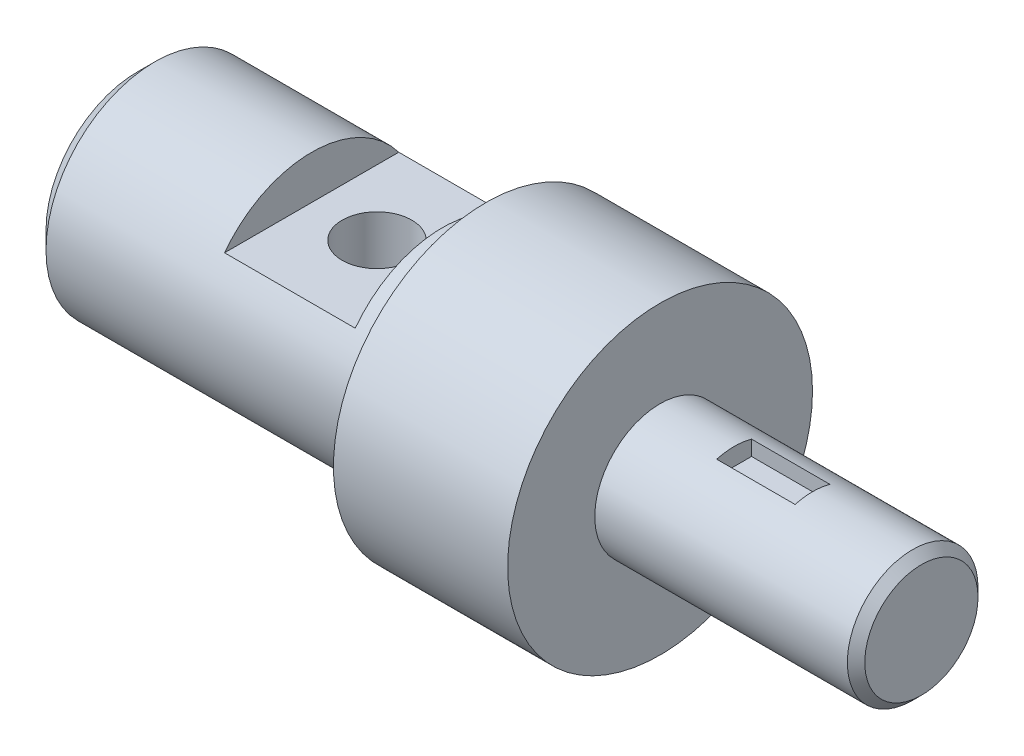
SolidWorks part; units mm, degrees
ref_plane "Спереди" through (0, 0, 0) normal (0, 0, 1) x (1, 0, 0)
ref_plane "Сверху" through (0, 0, 0) normal (0, 1, 0) x (1, 0, 0)
ref_plane "Справа" through (0, 0, 0) normal (1, 0, 0) x (0, 0, -1)
sketch "Эскиз1" plane through (0, 0, 0) normal (0, 0, 1) x (1, 0, 0)
  line L1 (0, 0) -> (0, 25)
  line L2 (0, 25) -> (80, 25)
  line L3 (80, 25) -> (80, 35)
  line L4 (80, 35) -> (120, 35)
  line L5 (120, 35) -> (120, 15)
  line L6 (120, 15) -> (180, 15)
  line L7 (180, 15) -> (180, 0)
  line L8 (0, 0) -> (180, 0)
  line L9 (0, 0) -> (-45.0163, 0) construction
  dimension "D1" = 70
  dimension "D2" = 50
  dimension "D3" = 30
  dimension "D4" = 180
  dimension "D5" = 80
  dimension "D6" = 60
revolve "Повернуть1" add sketch "Эскиз1" angle 360 about L9
sketch "Эскиз10" plane through (0, 0, 0) normal (0, 0, 1) x (1, 0, 0)
  line L0 (80, 25) -> (0, 25) construction
  line L1 (40, 25) -> (70, 25)
  line L2 (40, 25) -> (40, 15)
  line L3 (40, 15) -> (70, 15)
  line L4 (70, 25) -> (70, 15)
  line L5 (0, 25) -> (0, -25) construction
  line L6 (0, -25) -> (80, -25) construction
  dimension "D1" = 40
  dimension "D2" = 30
  dimension "D3" = 40
extrude "Вырез-Вытянуть7" cut sketch "Эскиз10" against normal through all both and the other way through all
ref_plane "Плоскость4" through (0, 35, 0) normal (0, 1, 0) x (1, 0, 0)
sketch "Эскиз14" plane through (0, 15, 0) normal (0, 1, 0) x (1, 0, 0)
  line L0 (40, 0) -> (70, 0) construction
  line L1 (40, -20) -> (40, 20) construction
  line L2 (70, 20) -> (70, -20) construction
  circle A0 centre (55, 0) radius 8
  point P8 (60.3804, 0)
  point P9 (55, 0)
  dimension "D1" = 16
extrude "Вырез-Вытянуть8" cut sketch "Эскиз14" against normal through all
sketch "Эскиз6" plane through (0, 0, 0) normal (0, 0, 1) x (1, 0, 0)
  line L0 (180, 15) -> (120, 15) construction
  line L1 (137, 15) -> (155, 15)
  line L2 (137, 15) -> (137, 11)
  line L3 (137, 11) -> (155, 11)
  line L4 (155, 15) -> (155, 11)
  line L5 (180, -15) -> (180, 15) construction
  dimension "D1" = 18
  dimension "D2" = 25
  dimension "D3" = 4
extrude "Вырез-Вытянуть4" cut sketch "Эскиз6" against normal mid plane 8
chamfer "Фаска3" distance 2 angle 45 1 edges at (180, 0, -15)
chamfer "Фаска4" distance 4 angle 45 1 edges at (0, 0, -25)
